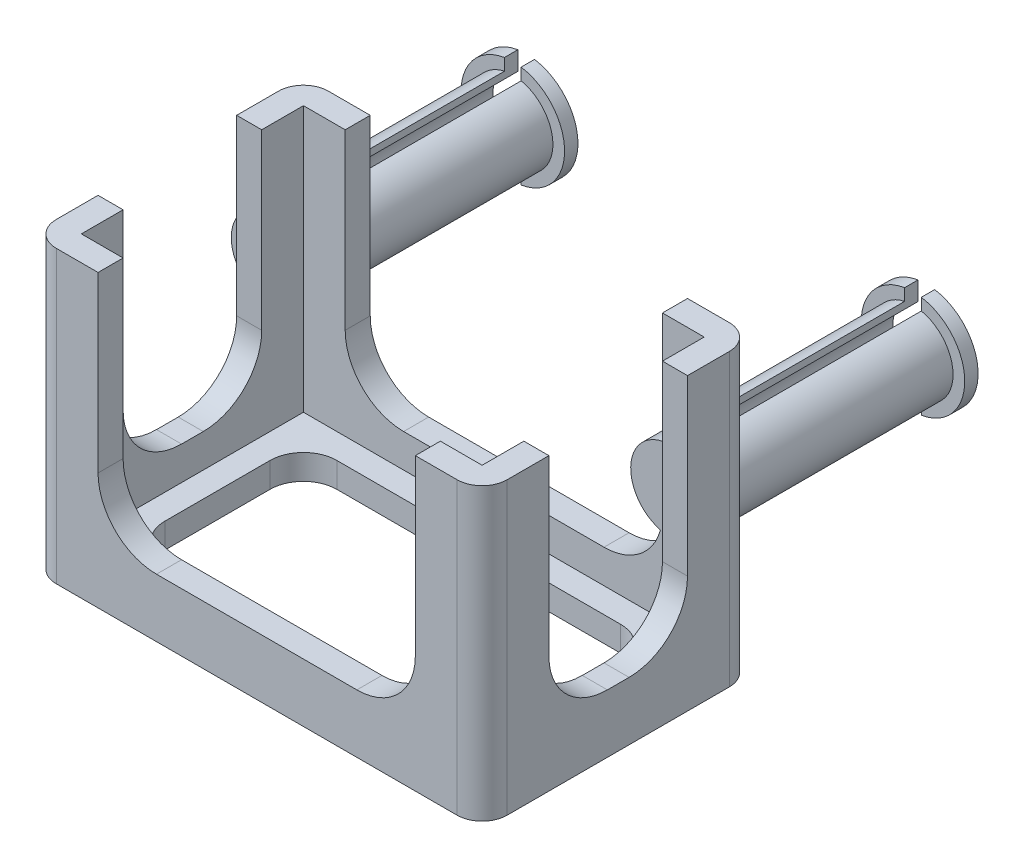
SolidWorks part; units mm, degrees
ref_plane "Front Plane" through (0, 0, 0) normal (0, 0, 1) x (1, 0, 0)
ref_plane "Top Plane" through (0, 0, 0) normal (0, 1, 0) x (1, 0, 0)
ref_plane "Right Plane" through (0, 0, 0) normal (1, 0, 0) x (0, 0, -1)
sketch "Sketch1" plane through (0, 0, 0) normal (0, 1, 0) x (1, 0, 0)
  line L1 (-38.3746, -21.1646) -> (-11.3746, -21.1646)
  line L2 (-38.3746, -21.1646) -> (-38.3746, -4.8646)
  line L3 (-38.3746, -4.8646) -> (-11.3746, -4.8646)
  line L4 (-11.3746, -21.1646) -> (-11.3746, -4.8646)
  dimension "D1" = 27
  dimension "D2" = 16.3
extrude "Boss-Extrude1" add sketch "Sketch1" along normal blind 17.4
sketch "Sketch2" plane through (0, 17.4, 0) normal (0, 1, 0) x (1, 0, 0)
  line L0 (-38.3746, -4.8646) -> (-38.3746, -21.1646) construction
  line L1 (-36.8746, -6.3646) -> (-12.8746, -6.3646)
  line L2 (-36.8746, -6.3646) -> (-36.8746, -19.6646)
  line L3 (-36.8746, -19.6646) -> (-12.8746, -19.6646)
  line L4 (-12.8746, -6.3646) -> (-12.8746, -19.6646)
  line L5 (-11.3746, -4.8646) -> (-38.3746, -4.8646) construction
  line L6 (-11.3746, -21.1646) -> (-11.3746, -4.8646) construction
  line L7 (-38.3746, -21.1646) -> (-11.3746, -21.1646) construction
  dimension "D1" = 1.5
  dimension "D2" = 1.5
  dimension "D3" = 1.5
  dimension "D4" = 1.5
extrude "Cut-Extrude1" cut sketch "Sketch2" against normal blind 15.9
sketch "Sketch3" plane through (0, 17.4, 0) normal (0, 1, 0) x (1, 0, 0)
  line L0 (-38.3746, -21.1646) -> (-11.3746, -21.1646) construction
  line L1 (-34.3746, -21.1646) -> (-15.3746, -21.1646)
  line L2 (-34.3746, -21.1646) -> (-34.3746, -4.8646)
  line L3 (-34.3746, -4.8646) -> (-15.3746, -4.8646)
  line L4 (-15.3746, -21.1646) -> (-15.3746, -4.8646)
  line L5 (-11.3746, -4.8646) -> (-38.3746, -4.8646) construction
  line L6 (-11.3746, -21.1646) -> (-11.3746, -4.8646) construction
  line L7 (-38.3746, -4.8646) -> (-38.3746, -21.1646) construction
  dimension "D1" = 4
  dimension "D2" = 4
extrude "Cut-Extrude2" cut sketch "Sketch3" against normal blind 13.9
sketch "Sketch4" plane through (0, 17.4, 0) normal (0, 1, 0) x (1, 0, 0)
  line L0 (-38.3746, -4.8646) -> (-38.3746, -21.1646) construction
  line L1 (-38.3746, -17.1646) -> (-11.3746, -17.1646)
  line L2 (-38.3746, -17.1646) -> (-38.3746, -8.8646)
  line L3 (-38.3746, -8.8646) -> (-11.3746, -8.8646)
  line L4 (-11.3746, -17.1646) -> (-11.3746, -8.8646)
  line L5 (-11.3746, -21.1646) -> (-11.3746, -4.8646) construction
  line L6 (-11.3746, -4.8646) -> (-15.3746, -4.8646) construction
  line L7 (-15.3746, -21.1646) -> (-11.3746, -21.1646) construction
  dimension "D1" = 4
  dimension "D2" = 4
extrude "Cut-Extrude3" cut sketch "Sketch4" against normal blind 13.9
sketch "Sketch6" plane through (0, 0, 0) normal (0, -1, 0) x (-1, 0, 0)
  line L0 (38.3746, -4.8646) -> (38.3746, -21.1646) construction
  line L1 (38.3746, -21.1646) -> (11.3746, -21.1646) construction
  line L2 (11.3746, -4.8646) -> (38.3746, -4.8646) construction
  circle A0 centre (32.8446, -9.0296) radius 3.69
  circle A1 centre (32.8446, -16.9996) radius 3.69
  circle A2 centre (16.9046, -9.0296) radius 3.69
  circle A3 centre (16.9046, -16.9996) radius 3.69
  dimension "D1" = 5.53
  dimension "D2" = 7.38
  dimension "D3" = 5.53
  dimension "D4" = 7.38
  dimension "D5" = 7.97
  dimension "D6" = 4.165
  dimension "D7" = 4.165
  dimension "D8" = 4.165
  dimension "D9" = 7.38
  dimension "D10" = 7.38
  dimension "D11" = 15.94
  dimension "D12" = 15.94
extrude "Boss-Extrude2" add sketch "Sketch6" along normal blind 2.38
sketch "Sketch7" plane through (0, -2.38, 0) normal (0, -1, 0) x (-1, 0, 0)
  line L0 (36.5346, -9.0296) -> (32.8446, -9.0296)
  line L1 (36.5346, -16.9996) -> (32.8446, -16.9996)
  line L2 (20.5946, -9.0296) -> (16.9046, -9.0296)
  line L3 (20.5946, -16.9996) -> (16.9046, -16.9996)
  circle A0 centre (32.8446, -9.0296) radius 3.69 construction
  circle A1 centre (32.8446, -16.9996) radius 3.69 construction
  circle A2 centre (16.9046, -9.0296) radius 3.69 construction
  circle A3 centre (16.9046, -16.9996) radius 3.69 construction
  circle A4 centre (32.8446, -9.0296) radius 3.1
  circle A5 centre (32.8446, -16.9996) radius 3.1
  circle A6 centre (16.9046, -16.9996) radius 3.1
  circle A7 centre (16.9046, -9.0296) radius 3.1
  dimension "D1" = 6.2
  dimension "D2" = 6.2
  dimension "D3" = 6.2
  dimension "D4" = 6.2
extrude "Cut-Extrude4" cut sketch "Sketch7" against normal blind 0.8
sketch "Sketch8" plane through (0, -1.58, 0) normal (0, -1, 0) x (-1, 0, 0)
  circle A0 centre (32.8446, -9.0296) radius 2.4
  circle A1 centre (32.8446, -16.9996) radius 2.4
  circle A2 centre (16.9046, -16.9996) radius 2.4
  circle A3 centre (16.9046, -9.0296) radius 2.4
  circle A4 centre (16.9046, -9.0296) radius 3.1 construction
  circle A5 centre (16.9046, -16.9996) radius 3.1 construction
  circle A6 centre (32.8446, -9.0296) radius 3.1 construction
  circle A7 centre (32.8446, -16.9996) radius 3.1 construction
  dimension "D1" = 0
  dimension "D2" = 0
  dimension "D3" = 0
  dimension "D4" = 0
  dimension "D5" = 4.8
  dimension "D6" = 4.8
  dimension "D7" = 4.8
  dimension "D8" = 4.8
extrude "Cut-Extrude5" cut sketch "Sketch8" against normal blind 4.8 contours A0 | A1 | A2 | A3
sketch "Sketch9" plane through (0, 1.5, 0) normal (0, 1, 0) x (1, 0, 0)
  line L0 (-35.2446, -16.9996) -> (-32.8446, -16.9996)
  line L1 (-35.2446, -9.0296) -> (-32.8446, -9.0296)
  line L2 (-19.3046, -16.9996) -> (-16.9046, -16.9996)
  line L3 (-19.3046, -9.0296) -> (-16.9046, -9.0296)
  circle A0 centre (-32.8446, -16.9996) radius 2.4 construction
  circle A1 centre (-32.8446, -9.0296) radius 2.4 construction
  circle A2 centre (-16.9046, -16.9996) radius 2.4 construction
  circle A3 centre (-16.9046, -9.0296) radius 2.4 construction
  circle A4 centre (-16.9046, -16.9996) radius 3.1
  circle A5 centre (-16.9046, -9.0296) radius 3.1
  circle A6 centre (-32.8446, -9.0296) radius 3.1
  circle A7 centre (-32.8446, -16.9996) radius 3.1
  dimension "D1" = 6.2
  dimension "D2" = 6.2
  dimension "D3" = 6.2
  dimension "D4" = 6.2
extrude "Cut-Extrude7" cut sketch "Sketch9" against normal blind 0.8
sketch "Sketch10" plane through (0, 1.5, 0) normal (0, 1, 0) x (1, 0, 0)
  line L0 (-31.261, -19.6646) -> (-18.4882, -19.6646) construction
  line L1 (-22.4046, -7.8646) -> (-27.3446, -7.8646)
  line L2 (-20.9046, -9.3646) -> (-20.9046, -16.6646)
  line L3 (-22.4046, -18.1646) -> (-27.3446, -18.1646)
  line L4 (-28.8446, -9.3646) -> (-28.8446, -16.6646)
  line L5 (-18.4882, -6.3646) -> (-31.261, -6.3646) construction
  circle A0 centre (-16.9046, -9.0296) radius 3.1 construction
  arc A1 (-31.261, -19.6646) -> (-34.4282, -19.6646) centre (-32.8446, -16.9996) ccw construction
  arc A2 (-27.3446, -7.8646) -> (-28.8446, -9.3646) centre (-27.3446, -9.3646) ccw
  arc A3 (-27.3446, -18.1646) -> (-28.8446, -16.6646) centre (-27.3446, -16.6646) cw
  arc A4 (-20.9046, -16.6646) -> (-22.4046, -18.1646) centre (-22.4046, -16.6646) cw
  arc A5 (-22.4046, -7.8646) -> (-20.9046, -9.3646) centre (-22.4046, -9.3646) cw
  dimension "D5" = 1.5
  dimension "D1" = 4
  dimension "D2" = 4
  dimension "D3" = 1.5
  dimension "D4" = 1.5
extrude "Cut-Extrude8" cut sketch "Sketch10" against normal blind 10
fillet "Fillet1" radius 3.5 1 edges at (-15.3746, 3.5, 5.6146)
fillet "Fillet2" radius 3.5 1 edges at (-15.3746, 3.5, 20.4146)
fillet "Fillet3" radius 3.5 1 edges at (-12.1246, 3.5, 17.1646)
fillet "Fillet4" radius 3.5 1 edges at (-12.1246, 3.5, 8.8646)
fillet "Fillet5" radius 3.5 1 edges at (-37.6246, 3.5, 8.8646)
fillet "Fillet6" radius 3.5 1 edges at (-37.6246, 3.5, 17.1646)
fillet "Fillet7" radius 3.5 1 edges at (-34.3746, 3.5, 5.6146)
fillet "Fillet8" radius 3.5 1 edges at (-34.3746, 3.5, 20.4146)
fillet "Fillet9" radius 1.5 1 edges at (-38.3746, 8.7, 21.1646)
fillet "Fillet10" radius 1.5 1 edges at (-38.3746, 8.7, 4.8646)
fillet "Fillet11" radius 1.5 1 edges at (-11.3746, 8.7, 4.8646)
fillet "Fillet12" radius 1.5 1 edges at (-11.3746, 8.7, 21.1646)
sketch "Sketch11" plane through (-11.3746, 0, 0) normal (1, 0, 0) x (0, 0, -1)
  line L0 (-19.6646, 0) -> (-6.3646, 0) construction
  line L1 (-21.1646, 0) -> (-1.1646, 0)
  line L2 (-21.1646, 0) -> (-21.1646, -4.5691)
  line L3 (-21.1646, -4.5691) -> (-1.1646, -4.5691)
  line L4 (-1.1646, 0) -> (-1.1646, -4.5691)
  dimension "D1" = 20
  dimension "D2" = 0
extrude "Cut-Extrude10" cut sketch "Sketch11" against normal blind 35 contours L2 L1 L4 L3
sketch "Sketch12" plane through (0, 0, 0) normal (0, -1, 0) x (-1, 0, 0)
  line L1 (37.9353, -20.7253) -> (11.814, -20.7253)
  line L2 (37.9353, -20.7253) -> (37.9353, -5.304)
  line L3 (37.9353, -5.304) -> (11.814, -5.304)
  line L4 (11.814, -20.7253) -> (11.814, -5.304)
  arc A0 (12.8746, -4.8646) -> (11.3746, -6.3646) centre (12.8746, -6.3646) ccw construction
  arc A1 (11.3746, -19.6646) -> (12.8746, -21.1646) centre (12.8746, -19.6646) ccw construction
  arc A3 (38.3746, -6.3646) -> (36.8746, -4.8646) centre (36.8746, -6.3646) ccw construction
  point P10 (11.814, -20.7253)
  point P14 (37.9353, -5.304)
  dimension "D1" = 0
  dimension "D2" = 0
extrude "Boss-Extrude3" add sketch "Sketch12" against normal blind 1.5
sketch "Sketch14" plane through (-4.4214, 0, 4.8646) normal (0, 0, -1) x (-1, 0, 0)
  circle A0 centre (34.3746, 8.4) radius 2.4
  dimension "D1" = 4.8
extrude "Boss-Extrude4" add sketch "Sketch14" against normal blind 1.5 and the other way blind 13.76
sketch "Sketch15" plane through (-4.4214, 0, -8.8954) normal (0, 0, -1) x (-1, 0, 0)
  circle A0 centre (34.3746, 8.4) radius 3.1
  circle A1 centre (34.3746, 8.4) radius 2.4 construction
  dimension "D1" = 0
  dimension "D2" = 0.7
extrude "Boss-Extrude6" add sketch "Sketch15" against normal blind 0.8
sketch "Sketch17" plane through (-4.4214, 0, -8.8954) normal (0, 0, -1) x (-1, 0, 0)
  circle A0 centre (34.3746, 8.4) radius 2
  circle A1 centre (34.3746, 8.4) radius 3.1 construction
  dimension "D1" = 0
  dimension "D2" = 4
extrude "Cut-Extrude11" cut sketch "Sketch17" against normal blind 11.8
sketch "Sketch18" plane through (-4.4214, 0, -8.8954) normal (0, 0, -1) x (-1, 0, 0)
  line L1 (33.8746, 12.4) -> (34.8746, 12.4)
  line L2 (33.8746, 12.4) -> (33.8746, 4.4)
  line L3 (33.8746, 4.4) -> (34.8746, 4.4)
  line L4 (34.8746, 12.4) -> (34.8746, 4.4)
  circle A0 centre (34.3746, 8.4) radius 3.1 construction
  dimension "D1" = 0.5
  dimension "D2" = 8
  dimension "D3" = 0.5
  dimension "D4" = 4
extrude "Cut-Extrude12" cut sketch "Sketch18" against normal blind 11.8
sketch "Sketch19" plane through (0, 0, 4.8646) normal (0, 0, -1) x (-1, 0, 0)
  line L0 (12.8746, 17.4) -> (15.3746, 17.4) construction
  circle A0 centre (14.876, 8.4) radius 2.4
  arc A1 (38.3746, 6.0373) -> (38.3746, 10.7627) centre (38.796, 8.4) ccw construction
  point P5 (0, 0)
  dimension "D1" = 4.8
  dimension "D2" = 23.92
  dimension "D3" = 9
extrude "Boss-Extrude7" add sketch "Sketch19" along normal blind 13.8038 and the other way blind 1.5
sketch "Sketch20" plane through (0, 0, -8.9392) normal (0, 0, -1) x (-1, 0, 0)
  circle A0 centre (14.876, 8.4) radius 3.1
  circle A1 centre (14.876, 8.4) radius 2.4 construction
  dimension "D1" = 0
  dimension "D2" = 0.7
extrude "Boss-Extrude8" add sketch "Sketch20" against normal blind 0.8
sketch "Sketch21" plane through (0, 0, -8.9392) normal (0, 0, -1) x (-1, 0, 0)
  circle A0 centre (14.876, 8.4) radius 2
  circle A1 centre (14.876, 8.4) radius 3.1 construction
  dimension "D1" = 0
  dimension "D2" = 1.1
extrude "Cut-Extrude13" cut sketch "Sketch21" against normal blind 11.8
sketch "Sketch22" plane through (0, 0, -8.9392) normal (0, 0, -1) x (-1, 0, 0)
  line L1 (14.376, 12.4) -> (15.376, 12.4)
  line L2 (14.376, 12.4) -> (14.376, 4.6517)
  line L3 (14.376, 4.6517) -> (15.376, 4.6517)
  line L4 (15.376, 12.4) -> (15.376, 4.6517)
  circle A0 centre (14.876, 8.4) radius 3.1 construction
  dimension "D1" = 4
  dimension "D2" = 0.5
  dimension "D3" = 0.5
extrude "Cut-Extrude14" cut sketch "Sketch22" against normal blind 11.8
sketch "Sketch23" plane through (0, 1.5, 0) normal (0, 1, 0) x (1, 0, 0)
  line L0 (-12.8746, -6.3646) -> (-36.8746, -6.3646) construction
  line L1 (-33.3746, -7.8646) -> (-16.3746, -7.8646)
  line L2 (-35.3746, -9.8646) -> (-35.3746, -16.1646)
  line L3 (-33.3746, -18.1646) -> (-16.3746, -18.1646)
  line L4 (-14.3746, -9.8646) -> (-14.3746, -16.1646)
  line L5 (-12.8746, -19.6646) -> (-12.8746, -6.3646) construction
  line L6 (-36.8746, -19.6646) -> (-12.8746, -19.6646) construction
  line L7 (-36.8746, -6.3646) -> (-36.8746, -19.6646) construction
  arc A0 (-35.3746, -16.1646) -> (-33.3746, -18.1646) centre (-33.3746, -16.1646) ccw
  arc A1 (-16.3746, -18.1646) -> (-14.3746, -16.1646) centre (-16.3746, -16.1646) ccw
  arc A2 (-16.3746, -7.8646) -> (-14.3746, -9.8646) centre (-16.3746, -9.8646) cw
  arc A3 (-33.3746, -7.8646) -> (-35.3746, -9.8646) centre (-33.3746, -9.8646) ccw
  dimension "D5" = 2
  dimension "D1" = 1.5
  dimension "D2" = 1.5
  dimension "D3" = 1.5
  dimension "D4" = 1.5
extrude "Cut-Extrude15" cut sketch "Sketch23" against normal blind 11.8
